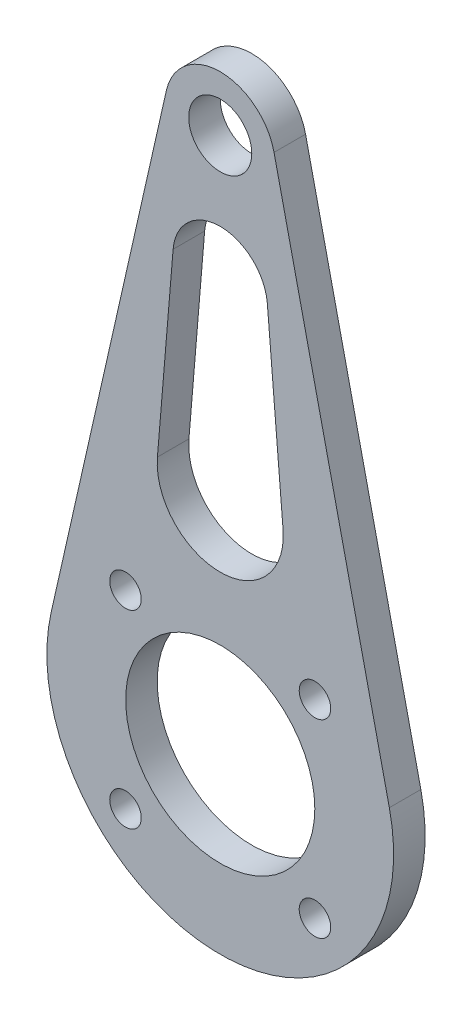
SolidWorks part; units mm, degrees
ref_plane "前视基准面" through (0, 0, 0) normal (0, 0, 1) x (1, 0, 0)
ref_plane "上视基准面" through (0, 0, 0) normal (0, 1, 0) x (1, 0, 0)
ref_plane "右视基准面" through (0, 0, 0) normal (1, 0, 0) x (0, 0, -1)
sketch "草图1" plane through (0, 0, 0) normal (0, 0, 1) x (1, 0, 0)
  line L0 (-3.4138, 34.7721) -> (-10.729, 2.4265)
  line L1 (0, -30.5072) -> (0, 63.4722) construction
  line L2 (3.4138, 34.7721) -> (10.729, 2.4265)
  line L3 (-2.9896, 26.25) -> (-3.9861, 14.3333)
  line L4 (2.9896, 26.25) -> (3.9861, 14.3333)
  circle A0 centre (0, 0) radius 6
  arc A1 (3.4138, 34.7721) -> (-3.4138, 34.7721) centre (0, 34) ccw
  arc A2 (2.9896, 26.25) -> (-2.9896, 26.25) centre (0, 26) ccw
  arc A3 (-3.9861, 14.3333) -> (3.9861, 14.3333) centre (0, 14) ccw
  circle A4 centre (0, 34) radius 2
  arc A5 (-10.729, 2.4265) -> (10.729, 2.4265) centre (0, 0) ccw
  dimension "D1" = 12
  dimension "D2" = 7
  dimension "D4" = 4
  dimension "D5" = 3
  dimension "D6" = 8
  dimension "D8" = 22
  dimension "D3" = 34
  dimension "D7" = 14
  dimension "D9" = 26
extrude "凸台-拉伸1" add sketch "草图1" along normal blind 2
sketch "草图2" plane through (0, 0, 0) normal (0, 0, 1) x (1, 0, 0)
  line L0 (-13.622, 0) -> (16.2004, 0) construction
  line L1 (0, 13.2853) -> (0, -16.8458) construction
  line L2 (0, -30.5072) -> (0, 63.4722) construction
  line L3 (0, 0) -> (12.0208, -12.0208) construction
  circle A0 centre (6.0104, -6.0104) radius 1
  dimension "D1" = 8.5
  dimension "D2" = 45
extrude "切除-拉伸8" cut sketch "草图2" along normal through all
pattern_circular "阵列(圆周)2" count 4 over 360 about axis through (0, 0, 0) along (0, 0, 1) of "切除-拉伸8"
